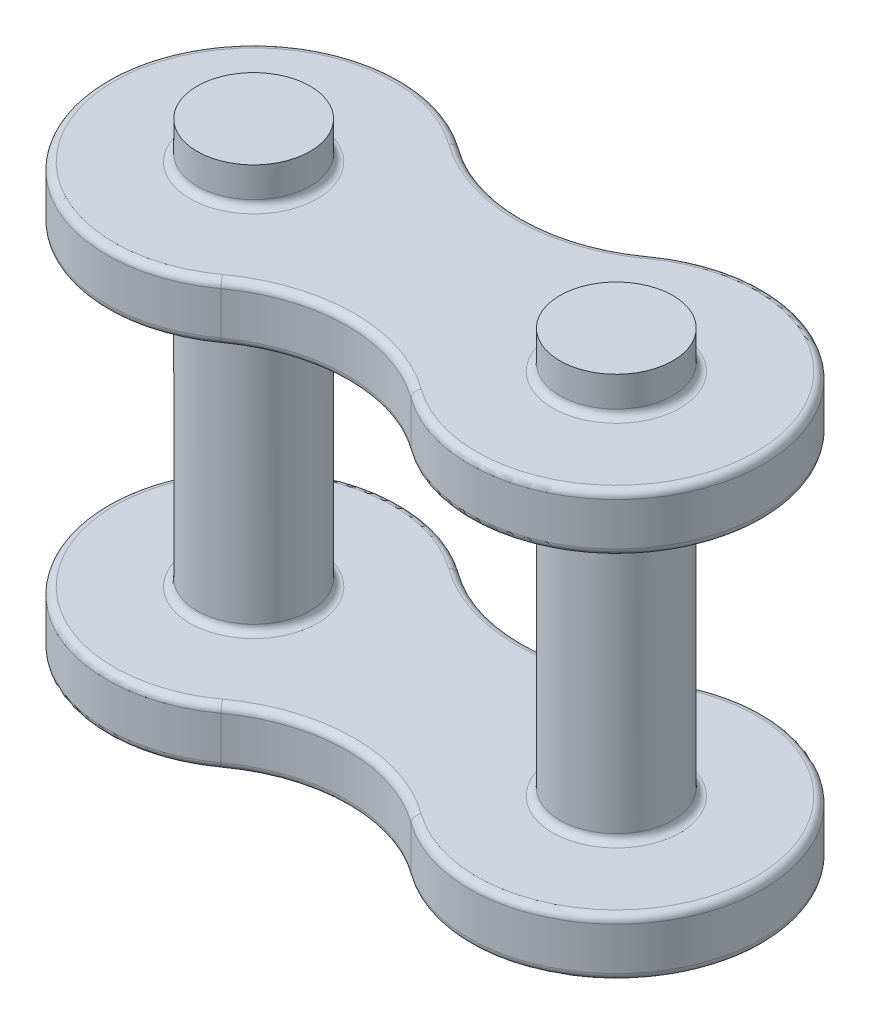
SolidWorks part; units mm, degrees
material "Alloy Steel"
ref_plane "X-Y Datum" through (0, 0, 0) normal (0, 0, 1) x (1, 0, 0)
ref_plane "X-Z Datum" through (0, 0, 0) normal (0, 1, 0) x (1, 0, 0)
ref_plane "Y-Z Datum" through (0, 0, 0) normal (1, 0, 0) x (0, 0, -1)
sketch "Sketch2" plane through (0, 0, 0) normal (0, 1, 0) x (1, 0, 0)
  line L0 (0, -9.7123) -> (0, 9.7123) construction
  line L1 (12.7033, 0) -> (-12.7033, 0) construction
  circle A0 centre (-6.35, 0) radius 1.98
  arc A1 (-3.3293, 4.163) -> (-3.3293, -4.163) centre (-6.35, 0) ccw
  circle A2 centre (6.35, 0) radius 1.98
  arc A3 (3.3293, 4.163) -> (3.3293, -4.163) centre (6.35, 0) cw
  arc A4 (-3.3293, 4.163) -> (3.3293, 4.163) centre (0, 8.7513) ccw
  arc A5 (-3.3293, -4.163) -> (3.3293, -4.163) centre (0, -8.7513) cw
  point P4 (0, 0)
  point P8 (0, 0)
  dimension "D1" = 10.287
  dimension "D2" = 3.96
  dimension "D3" = 6.35
extrude "Boss-Extrude1" add sketch "Sketch2" along normal mid plane 2.0066
ref_plane "Center Plane" through (0, 6.4389, 0) normal (0, 1, 0) x (1, 0, 0)
sketch "Sketch5" plane through (0, 6.4389, 0) normal (0, 1, 0) x (1, 0, 0)
  line L0 (0, -55) -> (0, 55) construction
  circle A0 centre (-6.35, 0) radius 1.98 construction
  circle A1 centre (-6.35, 0) radius 1.98
  circle A2 centre (6.35, 0) radius 1.98
extrude "Boss-Extrude2" add sketch "Sketch5" along normal mid plane 17.5006
fillet "Fillet1" radius 0.254 12 edges at (11.4935, -1.0033, 0) (0, -1.0033, 3.0824) (-11.4935, -1.0033, 0) (0, 1.0033, -3.0824) (11.4935, 1.0033, 0) (0, 1.0033, 3.0824) (-6.35, -1.0033, 1.98) (6.35, -1.0033, 1.98) (6.35, 1.0033, -1.98) (-6.35, 1.0033, 1.98) (0, -1.0033, -3.0824) (-11.4935, 1.0033, 0)
mirror "Mirror1" about plane through (0, 6.4389, 0) normal (0, 1, 0) of "Fillet1", "Boss-Extrude1"
ref_plane "Plane1" through (0, 6.4389, 0) normal (0, 1, 0) x (1, 0, 0)
ref_plane "Plane2" through (0, 6.4389, 0) normal (0, 1, 0) x (1, 0, 0)
sketch "Sketch6" plane through (0, 13.8811, 0) normal (0, 1, 0) x (1, 0, 0)
  circle A0 centre (6.35, 0) radius 1.98 construction
  circle A1 centre (-6.35, 0) radius 1.98 construction
  circle A2 centre (6.35, 0) radius 1.98 construction
  circle A3 centre (-6.35, 0) radius 1.98 construction
